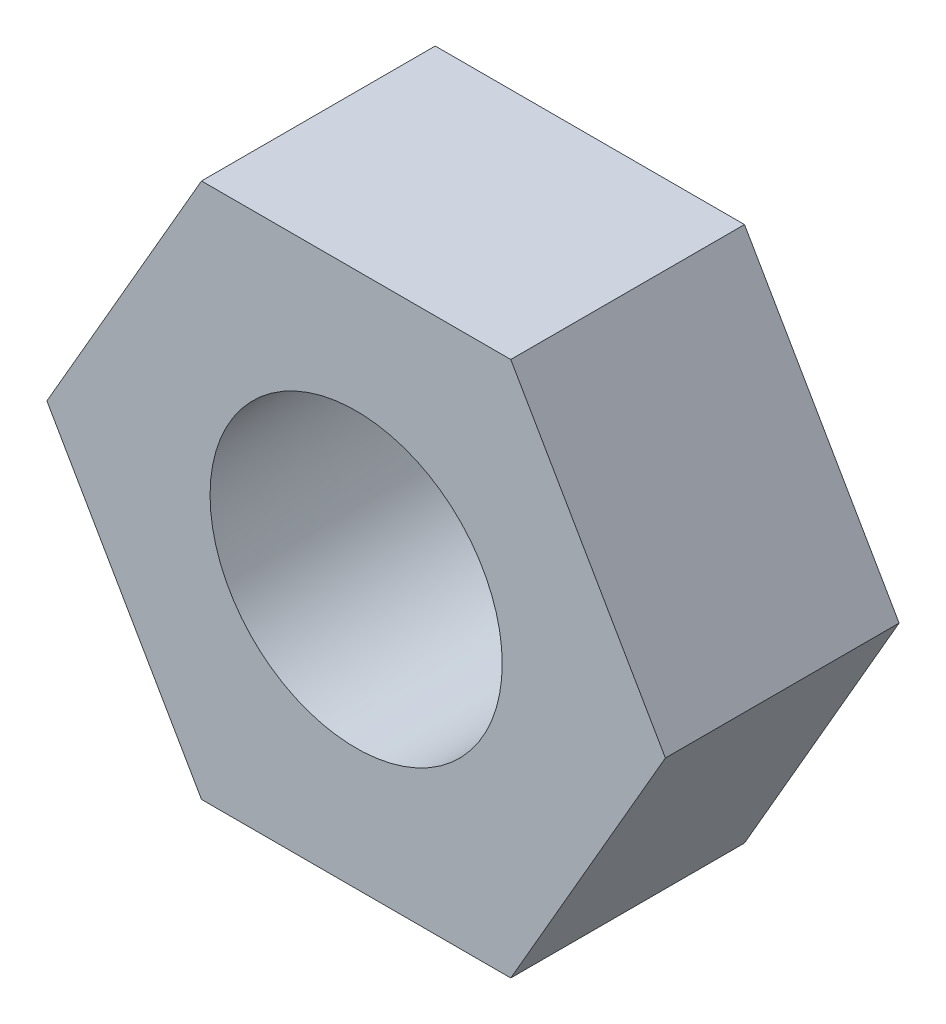
SolidWorks part; units mm, degrees
ref_plane "前视基准面" through (0, 0, 0) normal (0, 0, 1) x (1, 0, 0)
ref_plane "上视基准面" through (0, 0, 0) normal (0, 1, 0) x (1, 0, 0)
ref_plane "右视基准面" through (0, 0, 0) normal (1, 0, 0) x (0, 0, -1)
sketch "草图1" plane through (0, 0, 0) normal (0, 0, 1) x (1, 0, 0)
  line L1 (1.5877, -2.75) -> (3.1754, 0)
  line L2 (3.1754, 0) -> (1.5877, 2.75)
  line L3 (1.5877, 2.75) -> (-1.5877, 2.75)
  line L4 (-1.5877, 2.75) -> (-3.1754, 0)
  line L5 (-3.1754, 0) -> (-1.5877, -2.75)
  line L6 (-1.5877, -2.75) -> (1.5877, -2.75)
  circle A0 centre (0, 0) radius 2.75 construction
  dimension "D1" = 5.5
extrude "凸台-拉伸1" add sketch "草图1" along normal blind 2.4
sketch "草图2" plane through (0, 0, 2.4) normal (0, 0, 1) x (1, 0, 0)
  circle A0 centre (0, 0) radius 1.5
  dimension "D1" = 3
extrude "切除-拉伸1" cut sketch "草图2" against normal up to next
